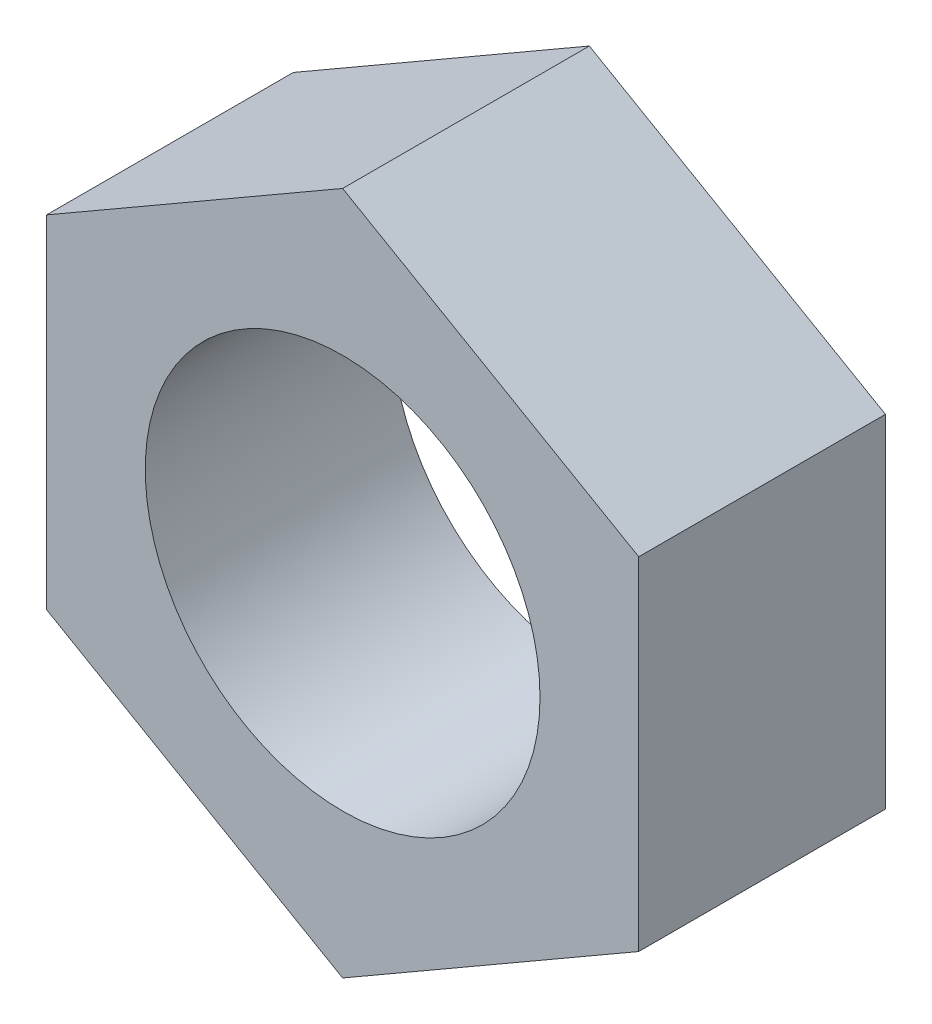
SolidWorks part; units mm, degrees
ref_plane "Front Plane" through (0, 0, 0) normal (0, 0, 1) x (1, 0, 0)
ref_plane "Top Plane" through (0, 0, 0) normal (0, 1, 0) x (1, 0, 0)
ref_plane "Right Plane" through (0, 0, 0) normal (1, 0, 0) x (0, 0, -1)
sketch "Sketch1" plane through (0, 0, 0) normal (0, 0, 1) x (1, 0, 0)
  line L0 (9.525, 5.4993) -> (-9.525, -5.4993) construction
  line L10 (-9.525, 5.4993) -> (-9.525, -5.4993)
  line L11 (-9.525, -5.4993) -> (0, -10.9985)
  line L12 (0, -10.9985) -> (9.525, -5.4993)
  line L13 (9.525, -5.4993) -> (9.525, 5.4993)
  line L14 (9.525, 5.4993) -> (0, 10.9985)
  line L15 (0, 10.9985) -> (-9.525, 5.4993)
  circle A0 centre (0, 0) radius 6.35
  dimension "D2" = 12.7
  dimension "D7" = 19.05
  dimension "D8" = 19.05
  dimension "D1" = 19.05
extrude "Extrude1" add sketch "Sketch1" along normal blind 7.9375
